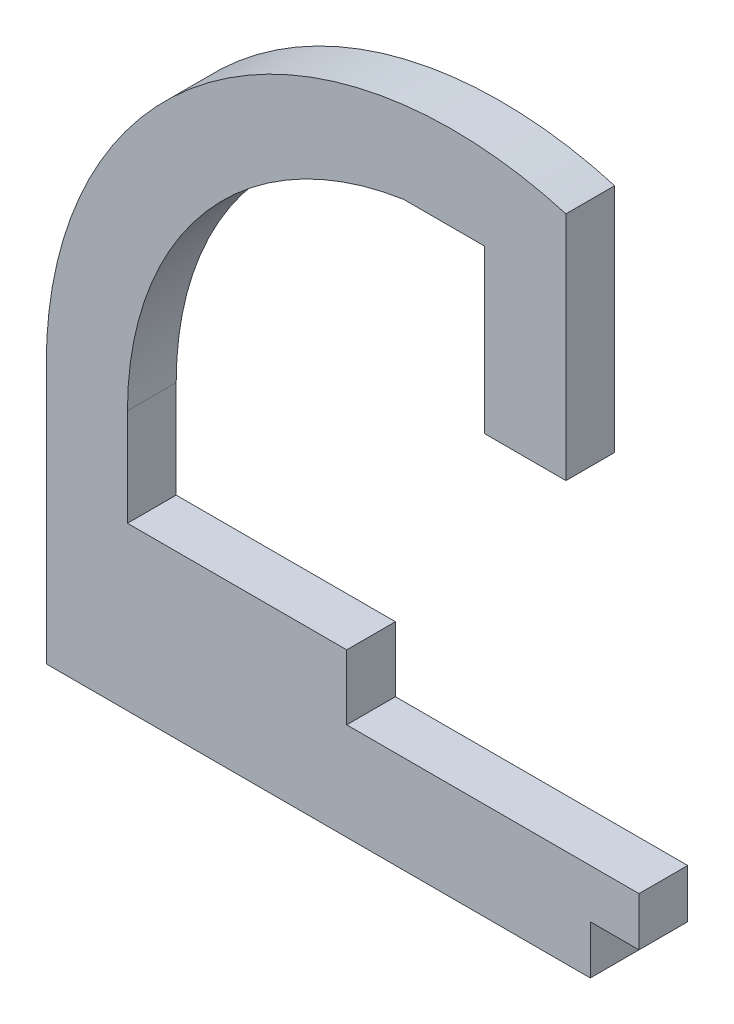
SolidWorks part; units mm, degrees
ref_plane "Спереди" through (0, 0, 0) normal (0, 0, 1) x (1, 0, 0)
ref_plane "Сверху" through (0, 0, 0) normal (0, 1, 0) x (1, 0, 0)
ref_plane "Справа" through (0, 0, 0) normal (1, 0, 0) x (0, 0, -1)
sketch "Эскиз2" plane through (0, 0, 0) normal (0, 0, 1) x (1, 0, 0)
  line L18 (67, 12) -> (67, 0) construction
  line L35 (10, 20) -> (10, 32)
  line L38 (54, 71.5474) -> (54, 51.5474)
  line L39 (54, 51.5474) -> (64, 51.5474)
  line L42 (10, 20) -> (37, 20)
  line L44 (64, 80) -> (64, 51.5474)
  line L45 (54, 71.5474) -> (44, 71.5474)
  line L47 (37, 20) -> (37, 12)
  line L48 (37, 12) -> (67, 12)
  line L56 (67, 12) -> (73, 12)
  line L57 (73, 12) -> (73, 6)
  line L58 (73, 6) -> (67, 6)
  line L59 (67, 6) -> (67, 0)
  line L64 (0, 32) -> (0, 0)
  line L65 (0, 0) -> (67, 0)
  arc A7 (44, 71.5474) -> (10, 32) centre (50, 32) ccw
  arc A9 (64, 80) -> (0, 32) centre (50, 32) ccw
  point P0 (0, 0)
  dimension "D3" = 67
  dimension "D4" = 12
  dimension "D5" = 10
  dimension "D8" = 80
  dimension "D9" = 27
  dimension "D2" = 32
  dimension "D6" = 3
  dimension "D7" = 10
  dimension "D10" = 20
  dimension "D11" = 28.4526
  dimension "D12" = 17
  dimension "D13" = 8
  dimension "D14" = 30
  dimension "D15" = 12
  dimension "D18" = 6
extrude "Бобышка-Вытянуть1" add sketch "Эскиз2" along normal blind 6
